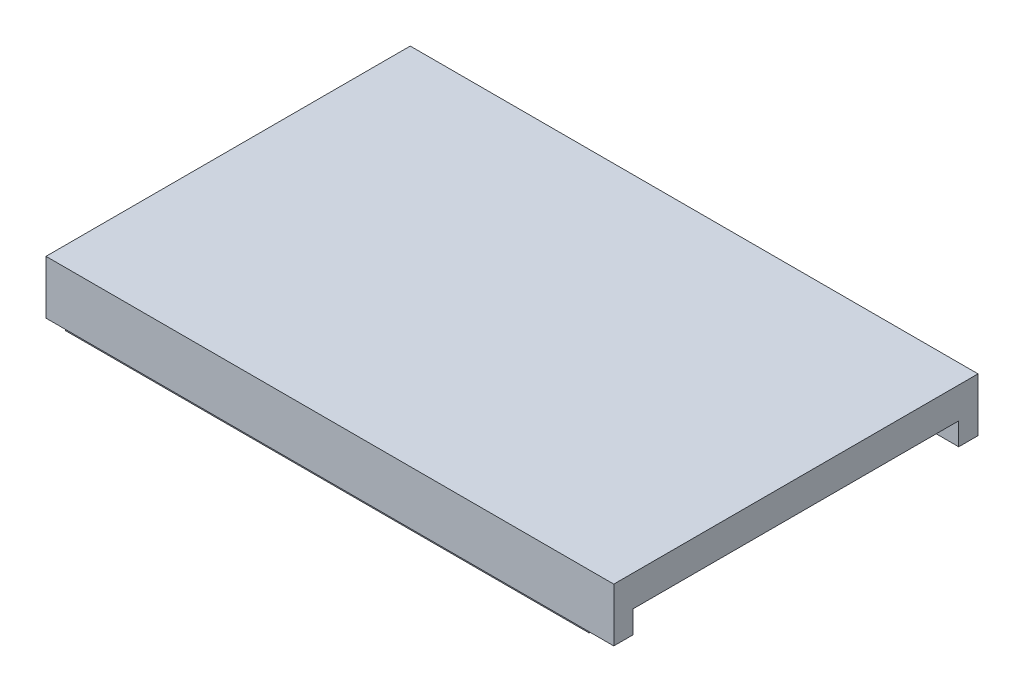
SolidWorks part; units mm, degrees
ref_plane "Front Plane" through (0, 0, 0) normal (0, 0, 1) x (1, 0, 0)
ref_plane "Top Plane" through (0, 0, 0) normal (0, 1, 0) x (1, 0, 0)
ref_plane "Right Plane" through (0, 0, 0) normal (1, 0, 0) x (0, 0, -1)
sketch "Sketch1" plane through (0, 0, 0) normal (0, 1, 0) x (1, 0, 0)
  line L1 (0, 0) -> (53, 0)
  line L2 (0, 0) -> (0, 34)
  line L3 (0, 34) -> (53, 34)
  line L4 (53, 0) -> (53, 34)
  dimension "D1" = 53
  dimension "D2" = 34
extrude "Boss-Extrude1" add sketch "Sketch1" along normal blind 5
sketch "Sketch2" plane through (0, 0, 0) normal (0, -1, 0) x (1, 0, 0)
  line L0 (0, -34) -> (0, 0) construction
  line L1 (1.2, -1.2) -> (49.8, -1.2)
  line L2 (1.2, -1.2) -> (1.2, -32.8)
  line L3 (1.2, -32.8) -> (49.8, -32.8)
  line L4 (49.8, -1.2) -> (49.8, -32.8)
  line L5 (0, 0) -> (53, 0) construction
  line L6 (53, -34) -> (0, -34) construction
  line L7 (53, 0) -> (53, -34) construction
  dimension "D1" = 1.2
  dimension "D2" = 1.2
  dimension "D3" = 1.2
  dimension "D4" = 3.2
extrude "Cut-Extrude1" cut sketch "Sketch2" against normal blind 3.5
sketch "Sketch3" plane through (0, 0, 0) normal (0, -1, 0) x (1, 0, 0)
  line L0 (49.8, -1.2) -> (1.2, -1.2)
  line L1 (1.2, -1.2) -> (1.2, -12)
  line L2 (1.2, -1.2) -> (1.2, -32.8) construction
  line L3 (1.2, -22) -> (1.2, -32.8)
  line L4 (1.2, -32.8) -> (49.8, -32.8)
  line L5 (49.8, -0.9) -> (0.9, -0.9)
  line L6 (0.9, -0.9) -> (0.9, -12)
  line L7 (0.9, -22) -> (0.9, -33.1)
  line L8 (0.9, -33.1) -> (49.8, -33.1)
  line L9 (49.8, -0.9) -> (49.8, -1.2)
  line L10 (0.9, -12) -> (1.2, -12)
  line L11 (0.9, -22) -> (1.2, -22)
  line L12 (49.8, -32.8) -> (49.8, -33.1)
  dimension "D1" = 10.8
  dimension "D2" = 10.8
  dimension "D3" = 0.3
  dimension "D4" = 0.3
extrude "Boss-Extrude2" add sketch "Sketch3" along normal blind 1
sketch "Sketch4" plane through (0, 0, 0) normal (0, -1, 0) x (1, 0, 0)
  line L0 (0, -34) -> (0, 0) construction
  line L1 (1.2, -12) -> (0, -12)
  line L2 (1.2, -12) -> (1.2, -22)
  line L3 (1.2, -22) -> (0, -22)
  line L4 (0, -12) -> (0, -22)
  dimension "D1" = 10
extrude "Cut-Extrude2" cut sketch "Sketch4" against normal blind 0.5
sketch "Sketch5" plane through (0, 0, 0) normal (0, -1, 0) x (1, 0, 0)
  line L0 (49.8, -32.8) -> (49.8, -1.2) construction
  line L1 (49.8, -1.8) -> (53, -1.8)
  line L2 (49.8, -1.8) -> (49.8, -32.2)
  line L3 (49.8, -32.2) -> (53, -32.2)
  line L4 (53, -1.8) -> (53, -32.2)
  line L5 (53, 0) -> (53, -34) construction
  line L6 (0, 0) -> (53, 0) construction
  dimension "D1" = 1.8
  dimension "D2" = 30.4
extrude "Cut-Extrude3" cut sketch "Sketch5" against normal blind 2.1
sketch "Sketch6" plane through (0, 3.5, 0) normal (0, -1, 0) x (1, 0, 0)
  line L1 (1.2, -1.2) -> (6.6, -1.2)
  line L2 (1.2, -1.2) -> (1.2, -6.6)
  line L3 (1.2, -6.6) -> (6.6, -6.6)
  line L4 (6.6, -1.2) -> (6.6, -6.6)
  line L5 (1.2, -32.8) -> (6.6, -32.8)
  line L6 (1.2, -32.8) -> (1.2, -28.5)
  line L7 (1.2, -28.5) -> (6.6, -28.5)
  line L8 (6.6, -32.8) -> (6.6, -28.5)
  dimension "D1" = 5.4
  dimension "D2" = 5.4
  dimension "D3" = 5.4
  dimension "D4" = 4.3
extrude "Boss-Extrude3" add sketch "Sketch6" along normal blind 3
sketch "Sketch7" plane through (0, 0.5, 0) normal (0, -1, 0) x (1, 0, 0)
  line L0 (5, -5) -> (5, -30.5) construction
  line L1 (0, -12) -> (0, 0) construction
  line L2 (0, 0) -> (53, 0) construction
  circle A0 centre (5, -5) radius 1.6
  circle A1 centre (5, -30.5) radius 1.6
  dimension "D4" = 3.2
  dimension "D5" = 3.2
  dimension "D1" = 5
  dimension "D2" = 5
  dimension "D3" = 25.5
extrude "Boss-Extrude4" add sketch "Sketch7" along normal blind 1.2
sketch "Sketch8" plane through (0, -0.7, 0) normal (0, -1, 0) x (1, 0, 0)
  line L0 (5, -5) -> (5, -30.5) construction
hole_wizard "M2 Tapped Hole1" positions "3DSketch2" profile "Sketch10" tap size "M2" standard "ISO"
sketch3d "3DSketch2"
  point P0 (5, -0.7, -5)
  point P3 (5, -0.7, -30.5)
sketch "Sketch10" plane through (5, -0.7, -5) normal (1, 0, 0) x (0, 0, -1)
  line L0 (0, 0) -> (0, 5.6807)
  line L1 (0, 5.6807) -> (0.8, 5.2)
  line L2 (0.8, 5.2) -> (0.8, 0)
  line L5 (0.8, 0) -> (0, 0)
  line L10 (0, 5.6807) -> (-0.8, 5.2) construction
  line L11 (0, -6.35) -> (0, 107.95) construction
  dimension "Tap Drill Dia." = 1.6
  dimension "Tap Drill Depth" = 5.2
  dimension "Drill Angle" = 118
cosmetic thread "Hole Thread1" parameters "D1"=4, "D2"=2
cosmetic thread "Hole Thread2" parameters "D1"=4, "D2"=2
